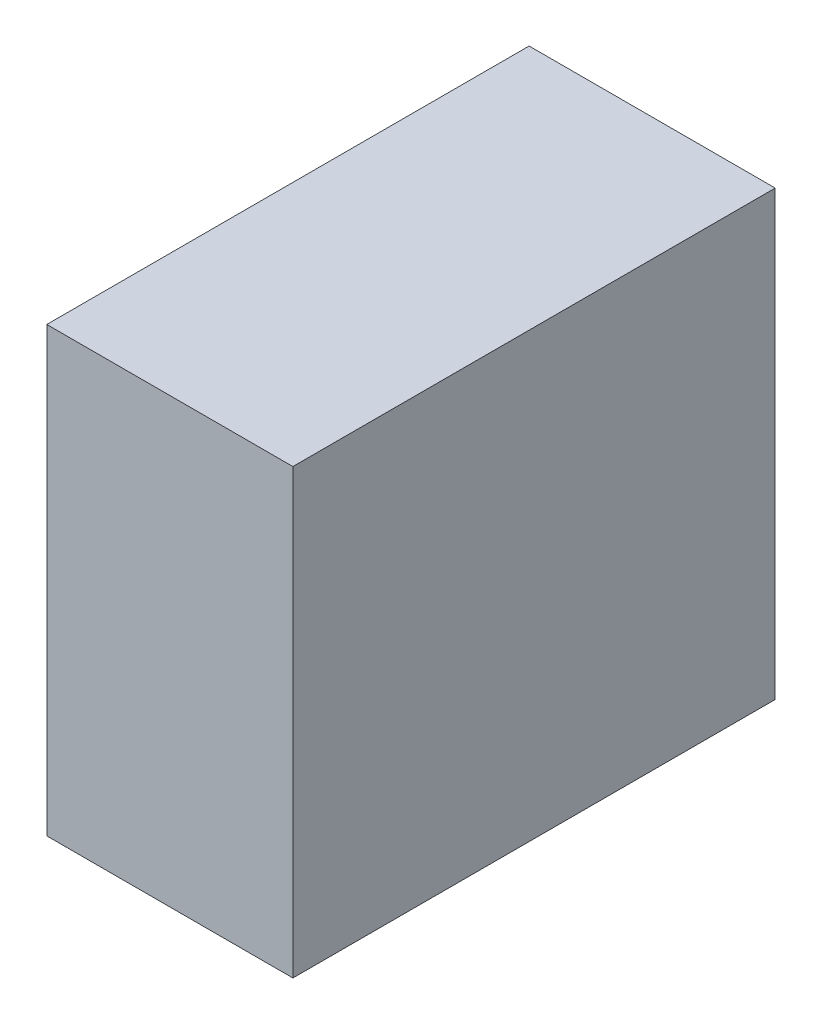
SolidWorks part; units mm, degrees
material "Porcelana cerâmica"
ref_plane "Plano frontal" through (0, 0, 0) normal (0, 0, 1) x (1, 0, 0)
ref_plane "Plano superior" through (0, 0, 0) normal (0, 1, 0) x (1, 0, 0)
ref_plane "Plano direito" through (0, 0, 0) normal (1, 0, 0) x (0, 0, -1)
sketch "Esboço1" plane through (0, 0, 0) normal (0, 0, 1) x (1, 0, 0)
  line L1 (0, 0) -> (50, 0)
  line L2 (0, 0) -> (0, 90)
  line L3 (0, 90) -> (50, 90)
  line L4 (50, 0) -> (50, 90)
  dimension "D1" = 90
  dimension "D2" = 50
extrude "Ressalto-extrusão1" add sketch "Esboço1" along normal blind 98
